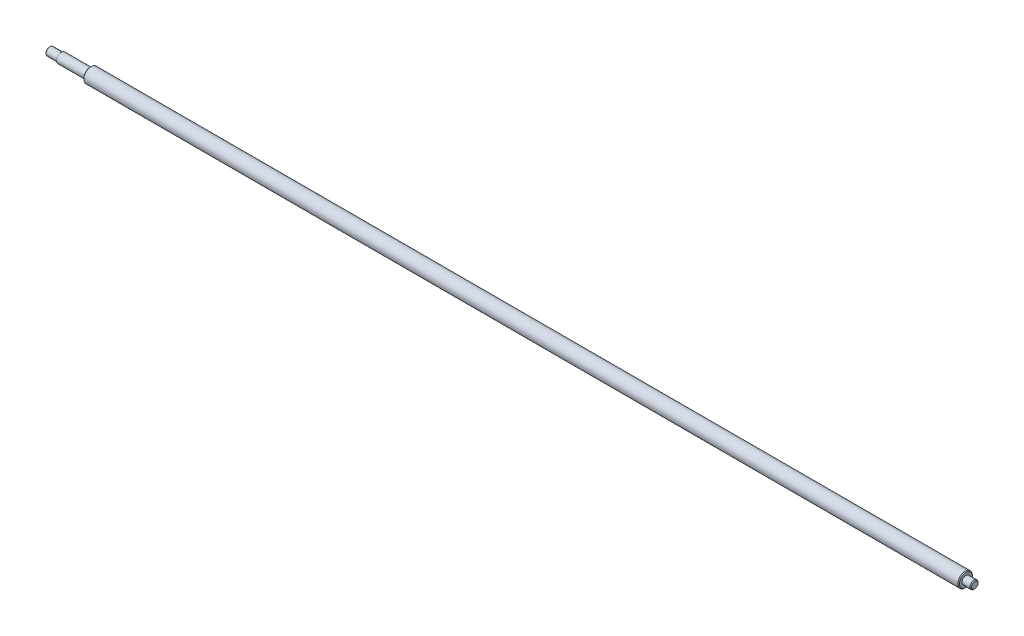
SolidWorks part; units mm, degrees
ref_plane "Front Plane" through (0, 0, 0) normal (0, 0, 1) x (1, 0, 0)
ref_plane "Top Plane" through (0, 0, 0) normal (0, 1, 0) x (1, 0, 0)
ref_plane "Right Plane" through (0, 0, 0) normal (1, 0, 0) x (0, 0, -1)
sketch "Sketch1" plane through (0, 0, 0) normal (0, 1, 0) x (1, 0, 0)
  line L0 (-222.9641, 0) -> (291.446, 0) construction
  line L1 (-208.4669, 0) -> (-208.4669, 4)
  line L2 (-207.4669, 5) -> (-193.4669, 5)
  line L3 (-193.4669, 5) -> (-193.4669, 6)
  line L4 (-193.4669, 6) -> (-157.4669, 6)
  line L5 (-157.4669, 6) -> (-157.4669, 8)
  line L6 (-156.4669, 9) -> (929.5331, 9)
  line L7 (930.5331, 8) -> (930.5331, 5)
  line L8 (930.5331, 5) -> (940.5331, 5)
  line L9 (941.5331, 4) -> (941.5331, 0)
  line L10 (-208.4669, 0) -> (941.5331, 0)
  line L11 (-208.4669, 4) -> (-207.4669, 5)
  line L12 (-157.4669, 8) -> (-156.4669, 9)
  line L13 (940.5331, 5) -> (941.5331, 4)
  line L14 (929.5331, 9) -> (930.5331, 8)
  point P4 (-208.4669, 5)
  point P9 (-157.4669, 9)
  point P10 (930.5331, 9)
  point P12 (941.5331, 5)
  dimension "D1" = 1088
  dimension "D2" = 9
  dimension "D3" = 5
  dimension "D4" = 6
  dimension "D5" = 10
  dimension "D6" = 15
  dimension "D7" = 36
  dimension "D8" = 11
revolve "Revolve1" add sketch "Sketch1" angle 360 about L0
sketch "Szkic1" plane through (-208.4669, 0, 0) normal (-1, 0, 0) x (0, 0, 1)
  point P0 (0, 0)
